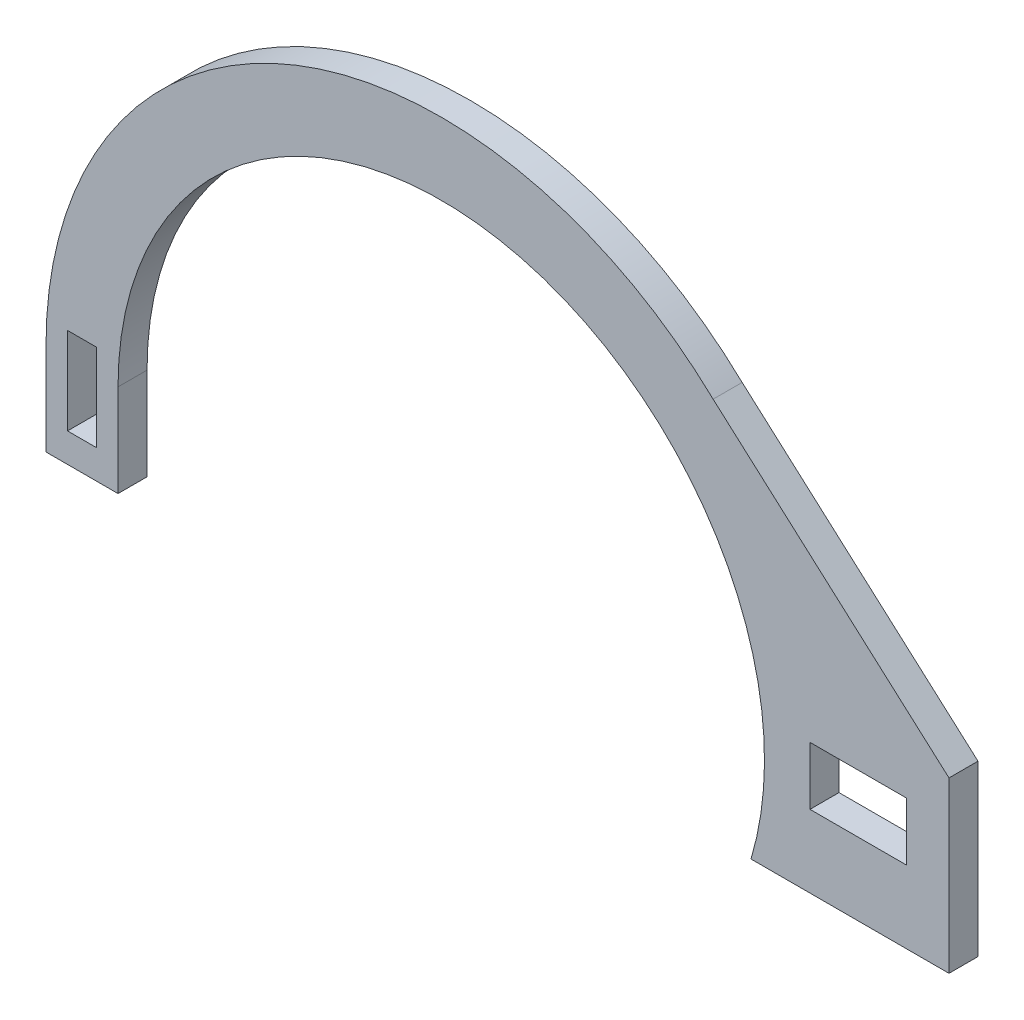
SolidWorks part; units mm, degrees
ref_plane "Front Plane" through (0, 0, 0) normal (0, 0, 1) x (1, 0, 0)
ref_plane "Top Plane" through (0, 0, 0) normal (0, 1, 0) x (1, 0, 0)
ref_plane "Right Plane" through (0, 0, 0) normal (1, 0, 0) x (0, 0, -1)
sketch "Sketch1" plane through (0, 0, 0) normal (0, 0, 1) x (1, 0, 0)
  line L0 (211.4286, -24.3178) -> (162.6532, 19.1274)
  line L1 (39.5813, -40.2071) -> (39.5813, -59.3178)
  line L2 (24.6864, -40.2071) -> (24.6864, -59.3178)
  line L4 (211.4286, -24.3178) -> (211.4286, -59.3178)
  line L6 (211.4286, -59.3178) -> (170.486, -59.3178)
  line L7 (24.6864, -59.3178) -> (39.5813, -59.3178)
  line L9 (202.6836, -32.3178) -> (182.6836, -32.3178)
  line L10 (202.6836, -32.3178) -> (202.6836, -44.3178)
  line L11 (202.6836, -44.3178) -> (182.6836, -44.3178)
  line L12 (182.6836, -32.3178) -> (182.6836, -44.3178)
  arc A0 (170.486, -59.3178) -> (39.5813, -40.2071) centre (106.4286, -40.2071) ccw
  arc A1 (162.6532, 19.1274) -> (24.6864, -40.2071) centre (106.4286, -40.2071) ccw
  dimension "D1" = 12
  dimension "D2" = 20
  dimension "D3" = 15
extrude "Boss-Extrude1" add sketch "Sketch1" along normal blind 6
sketch "Sketch2" plane through (0, 0, 0) normal (0, 0, -1) x (-1, 0, 0)
  line L3 (-35.1338, -35.3178) -> (-29.1338, -35.3178)
  line L4 (-35.1338, -35.3178) -> (-35.1338, -53.3178)
  line L5 (-35.1338, -53.3178) -> (-29.1338, -53.3178)
  line L6 (-29.1338, -35.3178) -> (-29.1338, -53.3178)
  line L7 (-35.1338, -35.3178) -> (-29.1338, -53.3178) construction
  line L8 (-35.1338, -53.3178) -> (-29.1338, -35.3178) construction
  point P4 (-32.1338, -44.3178)
  dimension "D2" = 6
  dimension "D3" = 18
extrude "Cut-Extrude1" cut sketch "Sketch2" against normal blind 10
